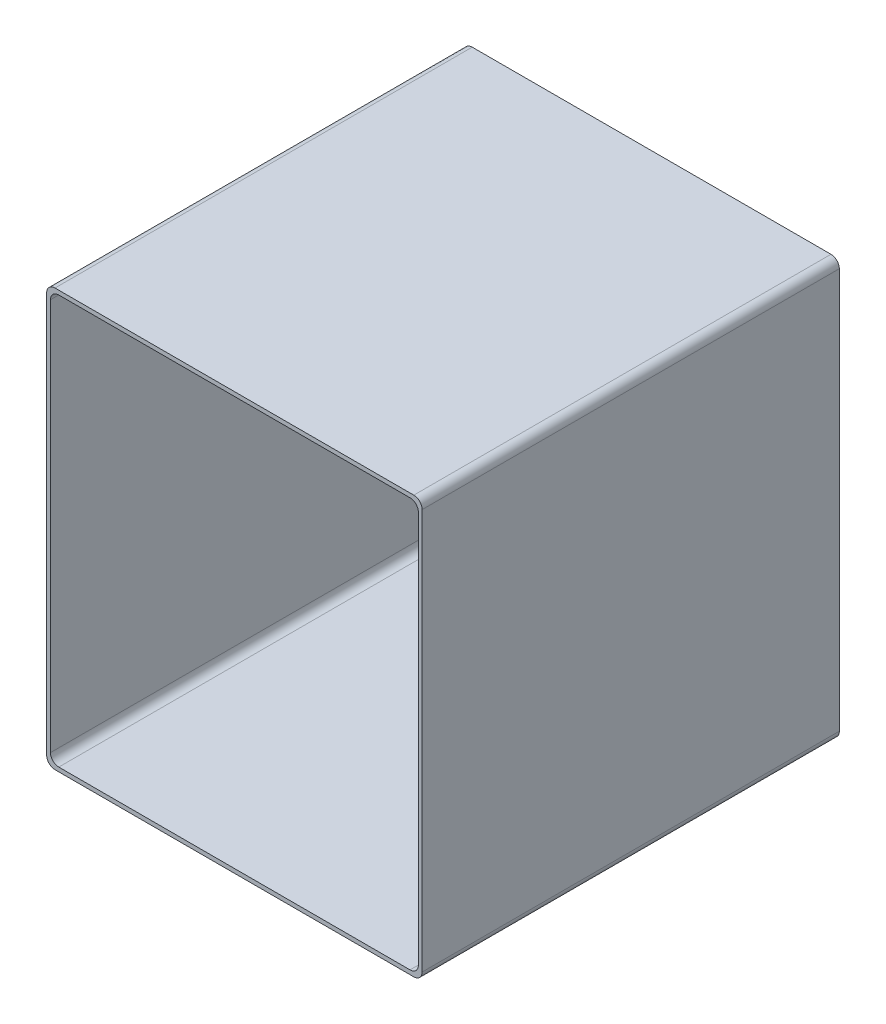
SolidWorks part; units mm, degrees
material "1060 Alloy"
ref_plane "Front Plane" through (0, 0, 0) normal (0, 0, 1) x (1, 0, 0)
ref_plane "Top Plane" through (0, 0, 0) normal (0, 1, 0) x (1, 0, 0)
ref_plane "Right Plane" through (0, 0, 0) normal (1, 0, 0) x (0, 0, -1)
sketch "Sketch2" plane through (0, 0, 0) normal (0, 0, 1) x (1, 0, 0)
  line L0 (0, 0) -> (450, 500) construction
  line L1 (0, 0) -> (450, 0)
  line L2 (0, 0) -> (0, 500)
  line L3 (0, 500) -> (450, 500)
  line L4 (450, 0) -> (450, 500)
  line L5 (4.5, 5) -> (445.5, 5)
  line L6 (4.5, 5) -> (4.5, 495)
  line L7 (4.5, 495) -> (445.5, 495)
  line L8 (445.5, 5) -> (445.5, 495)
  line L9 (0, 500) -> (450, 0) construction
  point P9 (20.2357, 22.4841)
  point P10 (433.6069, 18.2145)
  point P11 (0, 0)
  point P12 (0, 0)
  point P13 (430.707, 478.5633)
  point P14 (20.3732, 477.3631)
  dimension "D1" = 450
  dimension "D2" = 500
  dimension "D3" = 5
extrude "Boss-Extrude1" add sketch "Sketch2" along normal blind 500
fillet "Fillet1" radius 10 8 edges at (445.5, 5, 250) (445.5, 495, 250) (4.5, 495, 250) (4.5, 5, 250) (0, 0, 250) (0, 500, 250) (450, 0, 250) (450, 500, 250)
